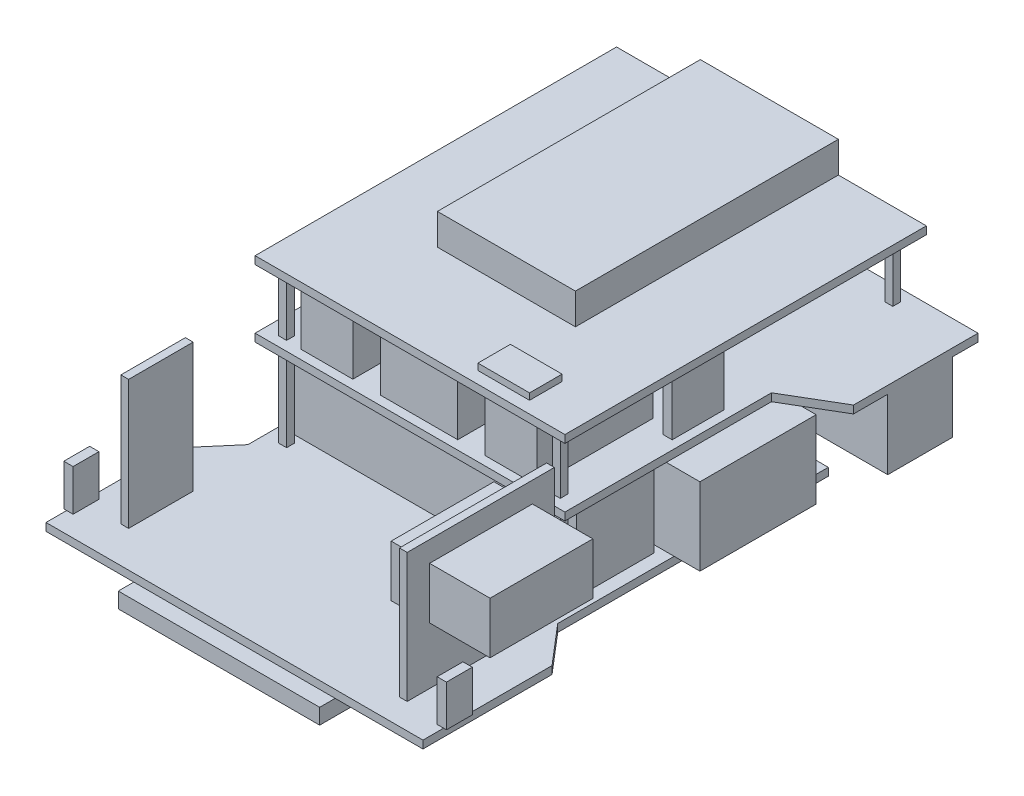
SolidWorks part; units mm, degrees
ref_plane "Front Plane" through (0, 0, 0) normal (0, 0, 1) x (1, 0, 0)
ref_plane "Top Plane" through (0, 0, 0) normal (0, 1, 0) x (1, 0, 0)
ref_plane "Right Plane" through (0, 0, 0) normal (1, 0, 0) x (0, 0, -1)
sketch "Sketch1" plane through (0, 0, 0) normal (0, 1, 0) x (1, 0, 0)
  line L0 (-73, -35) -> (-60, -19.8013)
  line L1 (60, -85) -> (-60, -85)
  line L2 (60, -19.8013) -> (60, 85)
  line L3 (60, 85) -> (-60, 85)
  line L4 (-60, -19.8013) -> (-60, 85)
  line L5 (60, -85) -> (-60, 85) construction
  line L6 (60, 85) -> (-60, -85) construction
  line L7 (0, 0) -> (0, -85) construction
  line L9 (-60, -85) -> (-73, -85)
  line L10 (-73, -35) -> (-73, -85)
  line L11 (60, -85) -> (73, -85)
  line L12 (73, -35) -> (73, -85)
  line L13 (73, -35) -> (60, -19.8013)
  point P0 (0, 0)
  dimension "D1" = 170
  dimension "D2" = 120
  dimension "D3" = 50
  dimension "D4" = 13
  dimension "D5" = 20
extrude "Boss-Extrude1" add sketch "Sketch1" along normal blind 3
sketch "Sketch2" plane through (0, 3, 0) normal (0, 1, 0) x (1, 0, 0)
  line L0 (0, 0) -> (0, 85) construction
  line L1 (60, 85) -> (-60, 85) construction
  line L2 (-60, 85) -> (-60, -19.8013) construction
  line L4 (-54.525, -13.335) -> (-51.475, -13.335)
  line L5 (-54.525, -13.335) -> (-54.525, -10.285)
  line L6 (-54.525, -10.285) -> (-51.475, -10.285)
  line L7 (-51.475, -13.335) -> (-51.475, -10.285)
  line L8 (-54.525, -13.335) -> (-51.475, -10.285) construction
  line L9 (-54.525, -10.285) -> (-51.475, -13.335) construction
  line L10 (51.475, -13.335) -> (54.525, -13.335)
  line L11 (51.475, -13.335) -> (51.475, -10.285)
  line L12 (51.475, -10.285) -> (54.525, -10.285)
  line L13 (54.525, -13.335) -> (54.525, -10.285)
  line L14 (51.475, -13.335) -> (54.525, -10.285) construction
  line L15 (51.475, -10.285) -> (54.525, -13.335) construction
  line L16 (52.475, 73.475) -> (55.525, 73.475)
  line L17 (52.475, 73.475) -> (52.475, 76.525)
  line L18 (52.475, 76.525) -> (55.525, 76.525)
  line L19 (55.525, 73.475) -> (55.525, 76.525)
  line L20 (52.475, 73.475) -> (55.525, 76.525) construction
  line L21 (52.475, 76.525) -> (55.525, 73.475) construction
  line L22 (-55.525, 73.475) -> (-52.475, 73.475)
  line L23 (-55.525, 73.475) -> (-55.525, 76.525)
  line L24 (-55.525, 76.525) -> (-52.475, 76.525)
  line L25 (-52.475, 73.475) -> (-52.475, 76.525)
  line L26 (-55.525, 73.475) -> (-52.475, 76.525) construction
  line L27 (-55.525, 76.525) -> (-52.475, 73.475) construction
  circle A0 centre (-53, -11.81) radius 1.525 construction
  circle A1 centre (-54, 75) radius 1.525 construction
  circle A2 centre (53, -11.81) radius 1.525 construction
  circle A3 centre (54, 75) radius 1.525 construction
  dimension "D1" = 10
  dimension "D2" = 3.05
  dimension "D3" = 6
  dimension "D4" = 3.05
  dimension "D5" = 7
  dimension "D6" = 86.81
extrude "Boss-Extrude2" add sketch "Sketch2" along normal blind 33
sketch "Sketch3" plane through (0, 36, 0) normal (0, 1, 0) x (1, 0, 0)
  line L0 (0, 52.99) -> (0, 122.99) construction
  line L1 (-60, -17.01) -> (60, -17.01)
  line L2 (-60, -17.01) -> (-60, 122.99)
  line L3 (-60, 122.99) -> (60, 122.99)
  line L4 (60, -17.01) -> (60, 122.99)
  line L5 (-60, -17.01) -> (60, 122.99) construction
  line L6 (-60, 122.99) -> (60, -17.01) construction
  line L7 (-60, 122.99) -> (-80, 122.99)
  line L8 (-80, 122.99) -> (-80, 74.7803)
  line L9 (-80, 74.7803) -> (-60, 62.99)
  line L10 (80, 74.7803) -> (60, 62.99)
  line L11 (80, 122.99) -> (80, 74.7803)
  line L12 (60, 122.99) -> (80, 122.99)
  line L14 (-54.525, -10.285) -> (-54.525, -13.335) construction
  point P0 (0, 52.99)
  point P19 (-54.525, -11.81)
  dimension "D1" = 120
  dimension "D2" = 140
  dimension "D3" = 60
  dimension "D4" = 30.52
  dimension "D5" = 20
  dimension "D6" = 5.2
extrude "Boss-Extrude3" add sketch "Sketch3" along normal blind 3 contours L8 L9 L2 L7 | L1 L4 L3 L2 | L12 L4 L10 L11
sketch "Sketch4" plane through (0, 39, 0) normal (0, 1, 0) x (1, 0, 0)
  line L0 (0, 0) -> (0, 32.3428) construction
  line L1 (-54.525, -13.335) -> (-51.475, -13.335)
  line L2 (-54.525, -13.335) -> (-54.525, -10.285)
  line L3 (-54.525, -10.285) -> (-51.475, -10.285)
  line L4 (-51.475, -13.335) -> (-51.475, -10.285)
  line L5 (-54.525, -13.335) -> (-51.475, -10.285) construction
  line L6 (-54.525, -10.285) -> (-51.475, -13.335) construction
  line L7 (-60, -17.01) -> (60, -17.01) construction
  line L8 (-60, -17.01) -> (-60, 62.99) construction
  line L9 (80, 122.99) -> (-80, 122.99) construction
  line L10 (-54.525, 115.465) -> (-51.475, 115.465)
  line L11 (-54.525, 115.465) -> (-54.525, 118.515)
  line L12 (-54.525, 118.515) -> (-51.475, 118.515)
  line L13 (-51.475, 115.465) -> (-51.475, 118.515)
  line L14 (-54.525, 115.465) -> (-51.475, 118.515) construction
  line L15 (-54.525, 118.515) -> (-51.475, 115.465) construction
  line L16 (54.525, -10.285) -> (51.475, -13.335) construction
  line L17 (54.525, -13.335) -> (51.475, -10.285) construction
  line L18 (51.475, -13.335) -> (51.475, -10.285)
  line L19 (54.525, -10.285) -> (51.475, -10.285)
  line L20 (54.525, -13.335) -> (54.525, -10.285)
  line L21 (54.525, -13.335) -> (51.475, -13.335)
  line L22 (54.525, 118.515) -> (51.475, 115.465) construction
  line L23 (54.525, 115.465) -> (51.475, 118.515) construction
  line L24 (51.475, 115.465) -> (51.475, 118.515)
  line L25 (54.525, 118.515) -> (51.475, 118.515)
  line L26 (54.525, 115.465) -> (54.525, 118.515)
  line L27 (54.525, 115.465) -> (51.475, 115.465)
  point P0 (-53, -11.81)
  point P12 (-53, 116.99)
  point P24 (53, -11.81)
  point P29 (53, 116.99)
  dimension "D1" = 3.05
  dimension "D2" = 5.2
  dimension "D3" = 7
  dimension "D4" = 6
extrude "Boss-Extrude4" add sketch "Sketch4" along normal blind 23
sketch "Sketch6" plane through (0, 62, 0) normal (0, 1, 0) x (1, 0, 0)
  line L0 (60, -17.01) -> (-60, -17.01)
  line L1 (60, -17.01) -> (60, 122.99)
  line L2 (-60, -17.01) -> (-60, 122.99)
  line L3 (60, 122.99) -> (-60, 122.99)
  line L4 (80, 122.99) -> (-80, 122.99) construction
extrude "Boss-Extrude5" add sketch "Sketch6" along normal blind 3
sketch "Sketch7" plane through (0, 36, 0) normal (0, -1, 0) x (1, 0, 0)
  line L0 (-80, -88.03) -> (-80, -113.03)
  line L1 (-80, -88.03) -> (-12, -88.03)
  line L2 (-80, -113.03) -> (-12, -113.03)
  line L3 (-12, -88.03) -> (-12, -113.03)
  line L4 (-80, -122.99) -> (-80, -74.7803) construction
  line L5 (0, 0) -> (0, -39.6137) construction
  line L6 (12, -88.03) -> (12, -113.03)
  line L7 (80, -113.03) -> (12, -113.03)
  line L8 (80, -88.03) -> (12, -88.03)
  line L9 (80, -88.03) -> (80, -113.03)
  line L10 (80, -122.99) -> (-80, -122.99) construction
  point P13 (-80, -100.53)
  dimension "D1" = 68
  dimension "D2" = 25
  dimension "D3" = 22.46
extrude "Boss-Extrude6" add sketch "Sketch7" along normal blind 27
sketch "Sketch9" plane through (0, 39, 0) normal (0, 1, 0) x (1, 0, 0)
  line L0 (-60, -17.01) -> (-60, 62.99) construction
  line L1 (-30.05, 55.88) -> (27.95, 55.88)
  line L2 (-30.05, 55.88) -> (-30.05, 115.88)
  line L3 (-30.05, 115.88) -> (27.95, 115.88)
  line L4 (27.95, 55.88) -> (27.95, 115.88)
  line L5 (-30.05, 55.88) -> (27.95, 115.88) construction
  line L6 (-30.05, 115.88) -> (27.95, 55.88) construction
  line L7 (80, 122.99) -> (-80, 122.99) construction
  line L8 (0, 0) -> (0, 23.7636) construction
  line L9 (-45.64, 31.48) -> (-25.64, 31.48)
  line L10 (-45.64, 31.48) -> (-45.64, -13.52)
  line L11 (-45.64, -13.52) -> (-25.64, -13.52)
  line L12 (-25.64, 31.48) -> (-25.64, -13.52)
  line L13 (-45.64, 31.48) -> (-25.64, -13.52) construction
  line L14 (-45.64, -13.52) -> (-25.64, 31.48) construction
  line L15 (-60, -17.01) -> (60, -17.01) construction
  line L16 (45.64, -13.52) -> (25.64, -13.52)
  line L17 (25.64, 31.48) -> (25.64, -13.52)
  line L18 (45.64, 31.48) -> (25.64, 31.48)
  line L19 (45.64, 31.48) -> (45.64, -13.52)
  line L21 (-15, 36.48) -> (15, 36.48)
  line L22 (-15, 36.48) -> (-15, -13.52)
  line L23 (-15, -13.52) -> (15, -13.52)
  line L24 (15, 36.48) -> (15, -13.52)
  line L25 (-15, 36.48) -> (15, -13.52) construction
  line L26 (-15, -13.52) -> (15, 36.48) construction
  point P0 (-1.05, 85.88)
  point P9 (-35.64, 8.98)
  point P23 (0, 11.48)
  dimension "D1" = 58
  dimension "D2" = 29.95
  dimension "D3" = 60
  dimension "D4" = 7.11
  dimension "D5" = 20
  dimension "D6" = 45
  dimension "D7" = 3.49
  dimension "D8" = 14.36
  dimension "D9" = 3.49
  dimension "D10" = 30
  dimension "D11" = 50
extrude "Boss-Extrude7" add sketch "Sketch9" along normal blind 20
sketch "Sketch10" plane through (0, 65, 0) normal (0, 1, 0) x (1, 0, 0)
  line L0 (-27.54, 122.99) -> (25.92, 122.99)
  line L1 (-27.54, 122.99) -> (-27.54, 21.14)
  line L2 (25.92, 122.99) -> (25.92, 21.14)
  line L3 (-27.54, 21.14) -> (25.92, 21.14)
  line L4 (60, 122.99) -> (-60, 122.99) construction
  line L5 (-60, 122.99) -> (-60, -17.01) construction
  dimension "D1" = 32.46
  dimension "D2" = 53.46
  dimension "D3" = 101.85
extrude "Boss-Extrude8" add sketch "Sketch10" along normal blind 12
sketch "Sketch11" plane through (0, 3, 0) normal (0, 1, 0) x (1, 0, 0)
  line L1 (-55, 22.5437) -> (55, 22.5437)
  line L2 (-55, 22.5437) -> (-55, -7.4563)
  line L3 (-55, -7.4563) -> (55, -7.4563)
  line L4 (55, 22.5437) -> (55, -7.4563)
  line L5 (-55, 22.5437) -> (55, -7.4563) construction
  line L6 (-55, -7.4563) -> (55, 22.5437) construction
  point P0 (0, 7.5437)
  dimension "D1" = 110
  dimension "D2" = 30
extrude "Boss-Extrude9" add sketch "Sketch11" along normal blind 32
sketch "Sketch12" plane through (0, 3, 0) normal (0, 1, 0) x (1, 0, 0)
  line L1 (-70, 25.2932) -> (70, 25.2932)
  line L2 (-70, 25.2932) -> (-70, 70.2932)
  line L3 (-70, 70.2932) -> (70, 70.2932)
  line L4 (70, 25.2932) -> (70, 70.2932)
  line L5 (-70, 25.2932) -> (70, 70.2932) construction
  line L6 (-70, 70.2932) -> (70, 25.2932) construction
  point P0 (0, 47.7932)
  dimension "D1" = 140
  dimension "D2" = 45
extrude "Boss-Extrude10" add sketch "Sketch12" along normal blind 30
sketch "Sketch13" plane through (0, 65, 0) normal (0, 1, 0) x (1, 0, 0)
  line L0 (60, -17.01) -> (60, 122.99) construction
  line L1 (21.68, -12.39) -> (41.68, -12.39)
  line L2 (21.68, -12.39) -> (21.68, 0.21)
  line L3 (21.68, 0.21) -> (41.68, 0.21)
  line L4 (41.68, -12.39) -> (41.68, 0.21)
  line L5 (21.68, -12.39) -> (41.68, 0.21) construction
  line L6 (21.68, 0.21) -> (41.68, -12.39) construction
  line L7 (-60, -17.01) -> (60, -17.01) construction
  point P0 (31.68, -6.09)
  dimension "D1" = 20
  dimension "D2" = 12.6
  dimension "D3" = 18.32
  dimension "D4" = 4.62
extrude "Boss-Extrude11" add sketch "Sketch13" along normal blind 2.5
sketch "Sketch14" plane through (0, 39, 0) normal (0, 1, 0) x (1, 0, 0)
  line L0 (60, -17.01) -> (60, 122.99) construction
  line L1 (56.55, 47.99) -> (52.95, 47.99)
  line L2 (56.55, 47.99) -> (56.55, 27.99)
  line L3 (56.55, 27.99) -> (52.95, 27.99)
  line L4 (52.95, 47.99) -> (52.95, 27.99)
  line L5 (56.55, 47.99) -> (52.95, 27.99) construction
  line L6 (56.55, 27.99) -> (52.95, 47.99) construction
  line L7 (-60, -17.01) -> (60, -17.01) construction
  line L8 (0, 0) -> (0, 51.8866) construction
  line L9 (-56.55, 27.99) -> (-52.95, 47.99) construction
  line L10 (-56.55, 47.99) -> (-52.95, 27.99) construction
  line L11 (-52.95, 47.99) -> (-52.95, 27.99)
  line L12 (-56.55, 27.99) -> (-52.95, 27.99)
  line L13 (-56.55, 47.99) -> (-56.55, 27.99)
  line L14 (-56.55, 47.99) -> (-52.95, 47.99)
  point P0 (54.75, 37.99)
  point P16 (-54.75, 37.99)
  dimension "D1" = 3.45
  dimension "D2" = 7.05
  dimension "D3" = 20
  dimension "D4" = 45
extrude "Boss-Extrude12" add sketch "Sketch14" along normal blind 20
sketch "Sketch15" plane through (0, 3, 0) normal (0, 1, 0) x (1, 0, 0)
  line L0 (73, -85) -> (73, -35) construction
  line L1 (70.5, -67) -> (74.1, -67)
  line L2 (70.5, -67) -> (70.5, -77)
  line L3 (70.5, -77) -> (74.1, -77)
  line L4 (74.1, -67) -> (74.1, -77)
  line L5 (-73, -85) -> (73, -85) construction
  line L6 (0, 0) -> (0, -32.3725) construction
  line L7 (-70.5, -67) -> (-74.1, -67)
  line L8 (-74.1, -67) -> (-74.1, -77)
  line L9 (-70.5, -77) -> (-74.1, -77)
  line L10 (-70.5, -67) -> (-70.5, -77)
  dimension "D1" = 1.1
  dimension "D2" = 2.5
  dimension "D3" = 10
  dimension "D4" = 8
extrude "Boss-Extrude13" add sketch "Sketch15" along normal blind 16
sketch "Sketch16" plane through (0, 3, 0) normal (0, 1, 0) x (1, 0, 0)
  line L0 (73, -67) -> (73, -35) construction
  line L1 (54, -18.1) -> (57, -18.1)
  line L2 (54, -18.1) -> (54, -75.1)
  line L3 (54, -75.1) -> (57, -75.1)
  line L4 (57, -18.1) -> (57, -75.1)
  line L5 (-73, -85) -> (73, -85) construction
  line L6 (-73, -35) -> (-73, -67) construction
  line L7 (-58, -46) -> (-55, -46)
  line L8 (-58, -46) -> (-58, -71)
  line L9 (-58, -71) -> (-55, -71)
  line L10 (-55, -46) -> (-55, -71)
  dimension "D1" = 19
  dimension "D2" = 3
  dimension "D3" = 57
  dimension "D4" = 9.9
  dimension "D5" = 15
  dimension "D6" = 3
  dimension "D7" = 25
  dimension "D8" = 14
extrude "Boss-Extrude14" add sketch "Sketch16" along normal blind 50
sketch "Sketch17" plane through (57, 0, 0) normal (1, 0, 0) x (0, 0, -1)
  line L0 (-75.1, 53) -> (-18.1, 53) construction
  line L1 (-66.4113, 45) -> (-26.6028, 45)
  line L2 (-66.4113, 45) -> (-66.4113, 25)
  line L3 (-66.4113, 25) -> (-26.6028, 25)
  line L4 (-26.6028, 45) -> (-26.6028, 25)
  dimension "D1" = 8
  dimension "D2" = 20
extrude "Boss-Extrude15" add sketch "Sketch17" along normal blind 23.4 and the other way blind 14.9
sketch "Sketch18" plane through (0, 0, 0) normal (0, -1, 0) x (1, 0, 0)
  line L0 (-73, 85) -> (73, 85) construction
  line L1 (-39, 66) -> (39, 66)
  line L2 (-39, 66) -> (-39, 91)
  line L3 (-39, 91) -> (39, 91)
  line L4 (39, 66) -> (39, 91)
  point P4 (0, 66)
  dimension "D1" = 25
  dimension "D2" = 78
  dimension "D3" = 6
extrude "Boss-Extrude16" add sketch "Sketch18" along normal blind 6
